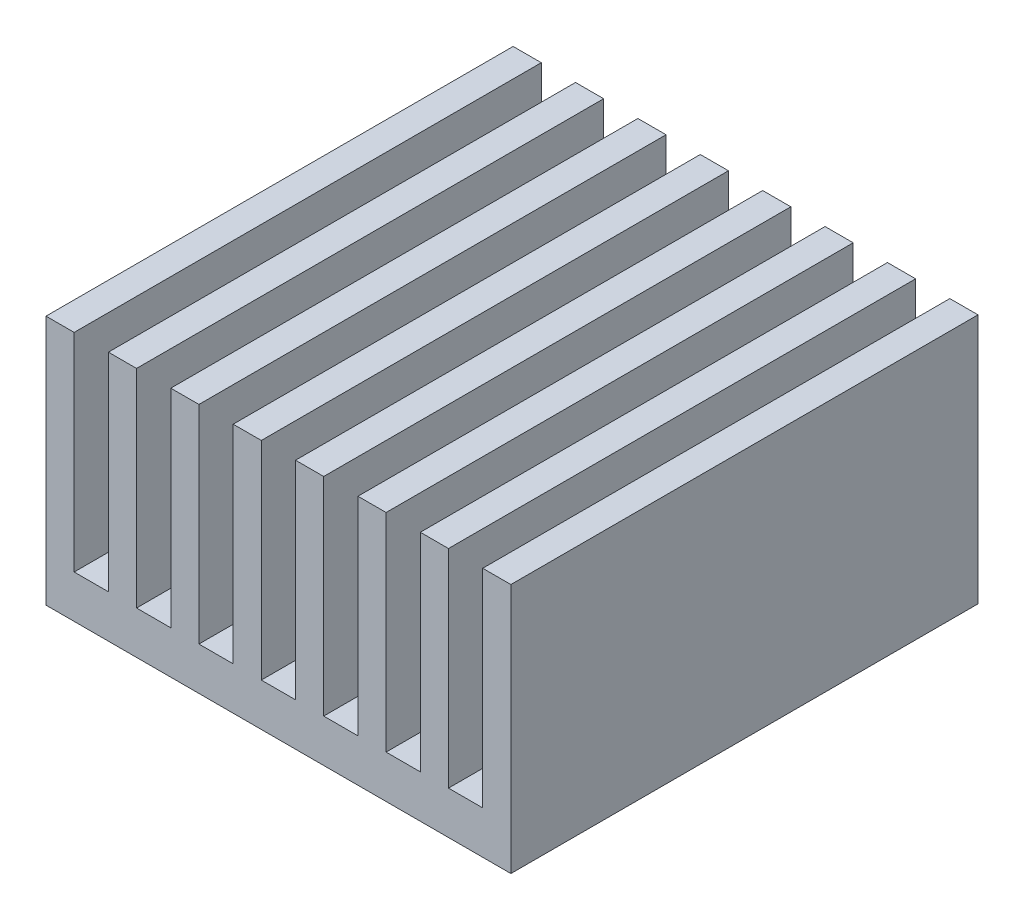
SolidWorks part; units mm, degrees
material "1060 Alloy"
ref_plane "Front Plane" through (0, 0, 0) normal (0, 0, 1) x (1, 0, 0)
ref_plane "Top Plane" through (0, 0, 0) normal (0, 1, 0) x (1, 0, 0)
ref_plane "Right Plane" through (0, 0, 0) normal (1, 0, 0) x (0, 0, -1)
sketch "Sketch1" plane through (0, 0, 0) normal (0, 1, 0) x (1, 0, 0)
  line L1 (0, 0) -> (16.51, 0)
  line L2 (0, 0) -> (0, 16.59)
  line L3 (0, 16.59) -> (16.51, 16.59)
  line L4 (16.51, 0) -> (16.51, 16.59)
  dimension "D1" = 16.51
  dimension "D2" = 16.59
extrude "Boss-Extrude1" add sketch "Sketch1" along normal blind 1.52
sketch "Sketch2" plane through (0, 1.52, 0) normal (0, 1, 0) x (1, 0, 0)
  line L21 (0, 0) -> (16.51, 0) construction
  line L22 (0, 16.59) -> (1, 16.59)
  line L23 (0, 16.59) -> (0, 0)
  line L24 (0, 0) -> (1, 0)
  line L25 (1, 16.59) -> (1, 0)
  line L26 (2.2157, 16.59) -> (2.2157, 0)
  line L27 (2.2157, 16.59) -> (3.2157, 16.59)
  line L28 (3.2157, 16.59) -> (3.2157, 0)
  line L29 (2.2157, 0) -> (3.2157, 0)
  line L30 (4.4314, 16.59) -> (4.4314, 0)
  line L31 (4.4314, 16.59) -> (5.4314, 16.59)
  line L32 (5.4314, 16.59) -> (5.4314, 0)
  line L33 (4.4314, 0) -> (5.4314, 0)
  line L34 (6.6471, 16.59) -> (6.6471, 0)
  line L35 (6.6471, 16.59) -> (7.6471, 16.59)
  line L36 (7.6471, 16.59) -> (7.6471, 0)
  line L37 (6.6471, 0) -> (7.6471, 0)
  line L38 (8.8629, 16.59) -> (8.8629, 0)
  line L39 (8.8629, 16.59) -> (9.8629, 16.59)
  line L40 (9.8629, 16.59) -> (9.8629, 0)
  line L41 (8.8629, 0) -> (9.8629, 0)
  line L42 (11.0786, 16.59) -> (11.0786, 0)
  line L43 (11.0786, 16.59) -> (12.0786, 16.59)
  line L44 (12.0786, 16.59) -> (12.0786, 0)
  line L45 (11.0786, 0) -> (12.0786, 0)
  line L46 (13.2943, 16.59) -> (13.2943, 0)
  line L47 (13.2943, 16.59) -> (14.2943, 16.59)
  line L48 (14.2943, 16.59) -> (14.2943, 0)
  line L49 (13.2943, 0) -> (14.2943, 0)
  line L50 (15.51, 16.59) -> (15.51, 0)
  line L51 (15.51, 16.59) -> (16.51, 16.59)
  line L52 (16.51, 16.59) -> (16.51, 0)
  line L53 (15.51, 0) -> (16.51, 0)
  line L54 (16.51, 0) -> (16.51, 16.59) construction
  dimension "D1" = 1
  dimension "D2" = 8
extrude "Boss-Extrude2" add sketch "Sketch2" along normal blind 7.37
